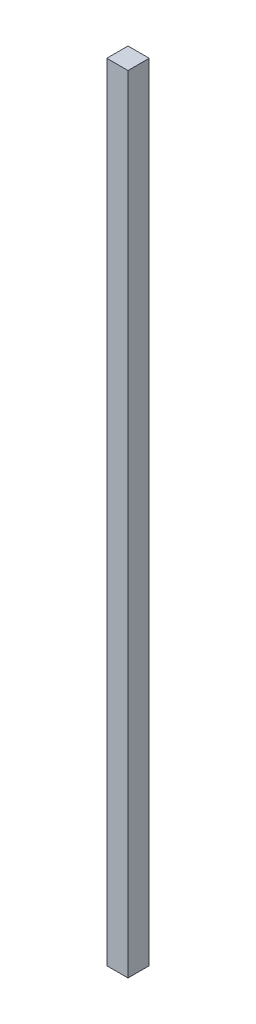
SolidWorks part; units mm, degrees
ref_plane "Front Plane" through (0, 0, 0) normal (0, 0, 1) x (1, 0, 0)
ref_plane "Top Plane" through (0, 0, 0) normal (0, 1, 0) x (1, 0, 0)
ref_plane "Right Plane" through (0, 0, 0) normal (1, 0, 0) x (0, 0, -1)
sketch "Sketch1" plane through (0, 0, 0) normal (0, 0, 1) x (1, 0, 0)
  line L0 (0, 0) -> (10, 0)
  line L1 (10, 0) -> (10, -370)
  line L2 (10, -370) -> (0, -370)
  line L3 (0, -370) -> (0, 0)
  dimension "D1" = 10
  dimension "D2" = 370
extrude "Boss-Extrude1" add sketch "Sketch1" along normal blind 10
